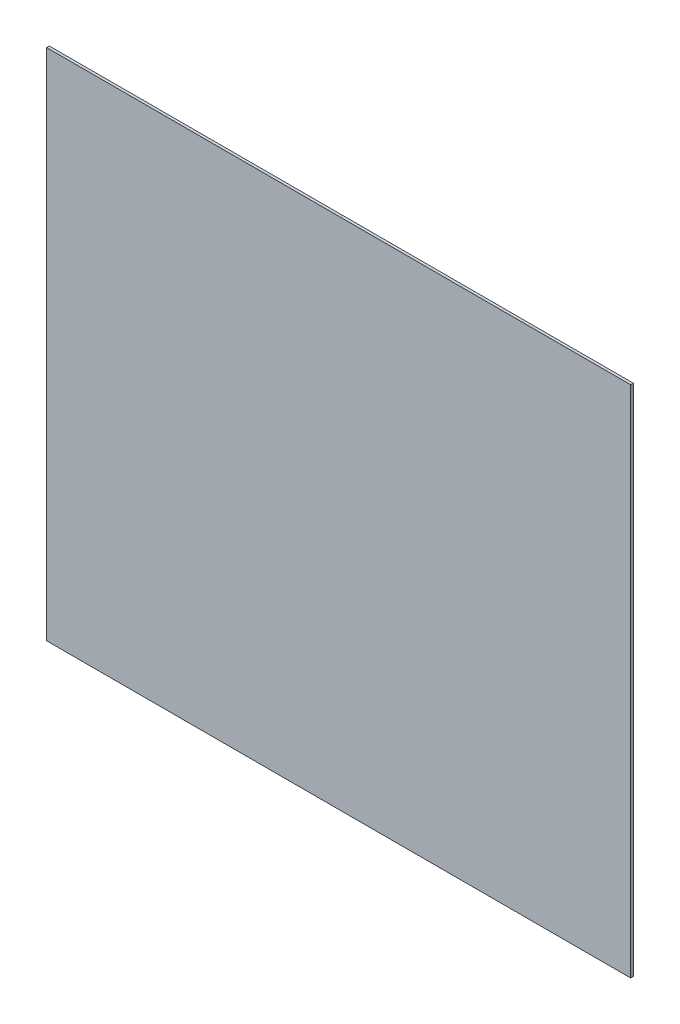
SolidWorks part; units mm, degrees
material "ABS"
ref_plane "Front Plane" through (0, 0, 0) normal (0, 0, 1) x (1, 0, 0)
ref_plane "Top Plane" through (0, 0, 0) normal (0, 1, 0) x (1, 0, 0)
ref_plane "Right Plane" through (0, 0, 0) normal (1, 0, 0) x (0, 0, -1)
sketch "Sketch1" plane through (0, 0, 0) normal (0, 0, 1) x (1, 0, 0)
  line L0 (0, 380) -> (0, 0) construction
  line L1 (-432, 380) -> (432, 380)
  line L2 (-432, 380) -> (-432, -380)
  line L3 (-432, -380) -> (432, -380)
  line L4 (432, 380) -> (432, -380)
  line L5 (0, 0) -> (0, -380) construction
  dimension "D1" = 864
  dimension "D2" = 760
extrude "Boss-Extrude1" add sketch "Sketch1" along normal blind 4
